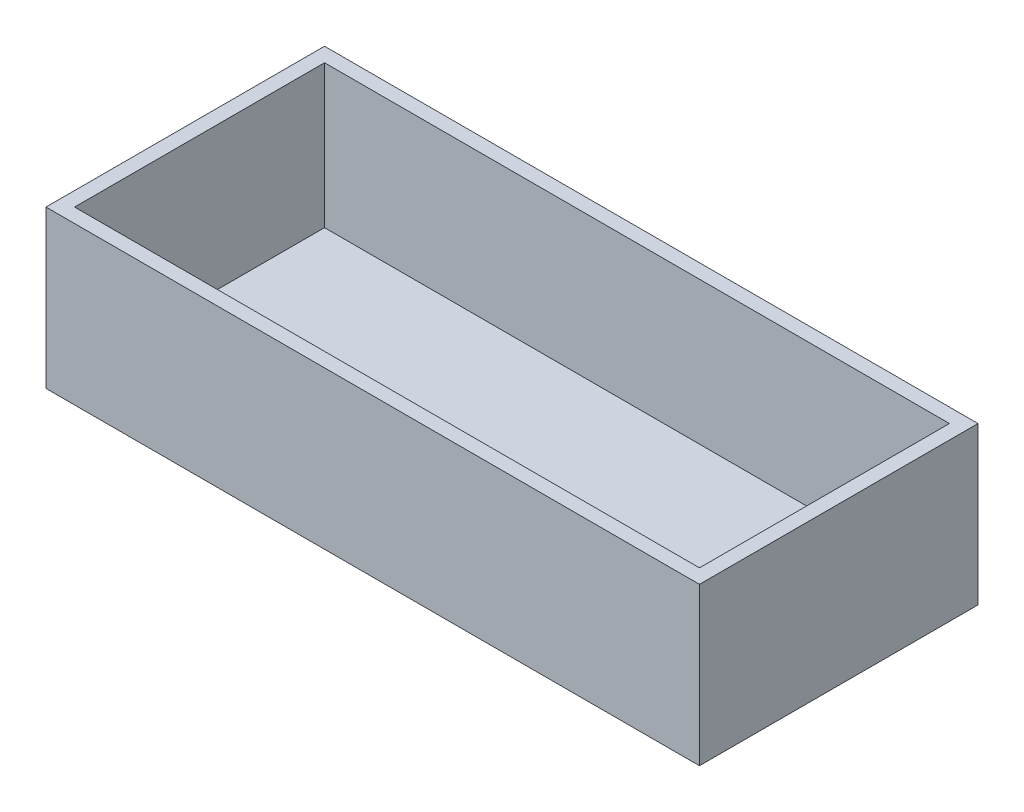
SolidWorks part; units mm, degrees
ref_plane "Front Plane" through (0, 0, 0) normal (0, 0, 1) x (1, 0, 0)
ref_plane "Top Plane" through (0, 0, 0) normal (0, 1, 0) x (1, 0, 0)
ref_plane "Right Plane" through (0, 0, 0) normal (1, 0, 0) x (0, 0, -1)
sketch "Sketch1" plane through (0, 0, 0) normal (0, 1, 0) x (1, 0, 0)
  line L0 (-31.8886, 14.6341) -> (59.6114, 14.6341)
  line L1 (-29.8886, 12.6341) -> (57.6114, 12.6341)
  line L2 (-29.8886, 12.6341) -> (-29.8886, -22.3659)
  line L3 (-29.8886, -22.3659) -> (57.6114, -22.3659)
  line L4 (57.6114, 12.6341) -> (57.6114, -22.3659)
  line L5 (59.6114, 14.6341) -> (59.6114, -24.3659)
  line L6 (-31.8886, -24.3659) -> (59.6114, -24.3659)
  line L7 (-31.8886, 14.6341) -> (-31.8886, -24.3659)
  dimension "D1" = 87.5
  dimension "D2" = 35
  dimension "D3" = 2
extrude "Boss-Extrude1" add sketch "Sketch1" along normal blind 20
sketch "Sketch2" plane through (0, 0, 0) normal (0, -1, 0) x (1, 0, 0)
  line L1 (-31.8886, 24.3659) -> (59.6114, 24.3659)
  line L2 (-31.8886, 24.3659) -> (-31.8886, -14.6341)
  line L3 (-31.8886, -14.6341) -> (59.6114, -14.6341)
  line L4 (59.6114, 24.3659) -> (59.6114, -14.6341)
extrude "Boss-Extrude2" add sketch "Sketch2" along normal blind 2
